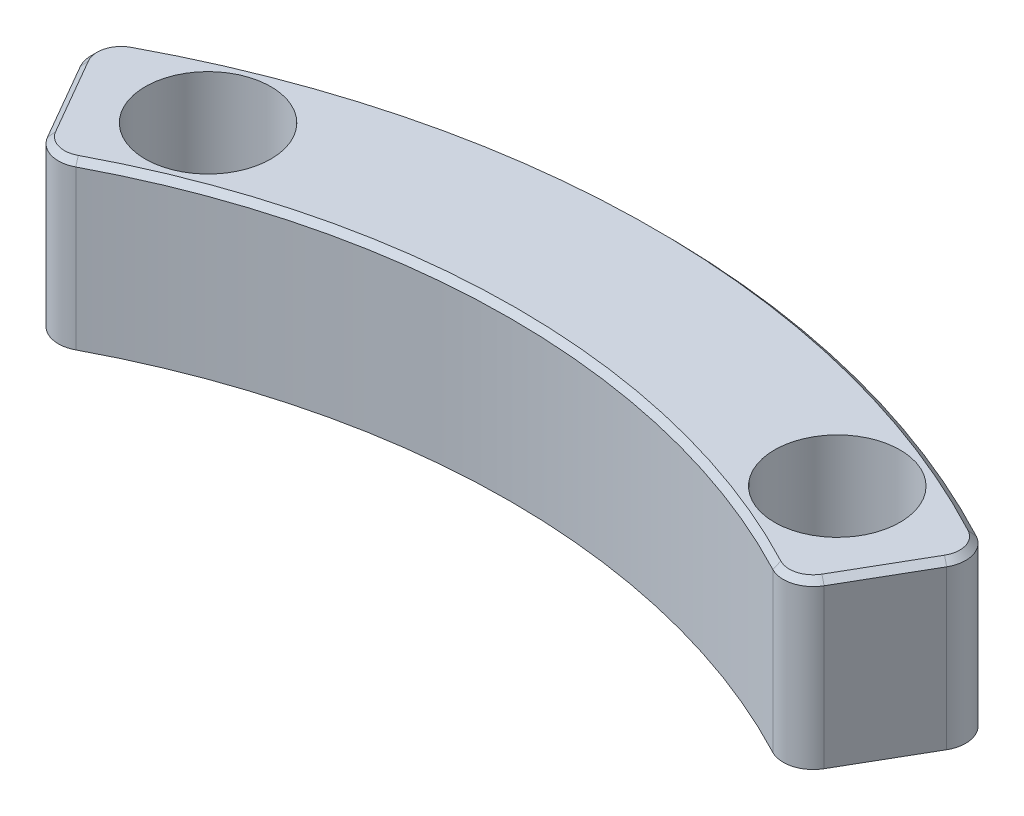
SolidWorks part; units mm, degrees
material "6061 合金"
ref_plane "前视基准面" through (0, 0, 0) normal (0, 0, 1) x (1, 0, 0)
ref_plane "上视基准面" through (0, 0, 0) normal (0, 1, 0) x (1, 0, 0)
ref_plane "右视基准面" through (0, 0, 0) normal (1, 0, 0) x (0, 0, -1)
other "Configuration Table"
sketch "草图1" plane through (0, 0, 0) normal (0, 1, 0) x (1, 0, 0)
  line L0 (0, 30) -> (0, 0) construction
  line L1 (0, 0) -> (-15, 25.9808) construction
  line L2 (0, 0) -> (15, 25.9808) construction
  line L3 (-15, 25.9808) -> (-12.5, 21.6506)
  line L4 (15, 25.9808) -> (12.5, 21.6506)
  arc A0 (15, 25.9808) -> (-15, 25.9808) centre (0, 0) ccw
  arc A1 (12.5, 21.6506) -> (-12.5, 21.6506) centre (0, 0) ccw
  dimension "D1" = 60
  dimension "D2" = 50
  dimension "D3" = 60
extrude "凸台-拉伸1" add sketch "草图1" along normal blind 5.5
sketch "草图2" plane through (0, 5.5, 0) normal (0, 1, 0) x (1, 0, 0)
  line L0 (0, 0) -> (-10.5238, 25.4067) construction
  line L1 (0, 27.5) -> (0, 0) construction
  line L2 (0, 0) -> (10.5238, 25.4067) construction
  circle A0 centre (0, 0) radius 27.5 construction
  circle A1 centre (-10.5238, 25.4067) radius 2.1
  circle A2 centre (10.5238, 25.4067) radius 2.1
  dimension "D1" = 55
  dimension "D3" = 4.2
  dimension "D4" = 4.2
  dimension "D2" = 45
extrude "切除-拉伸2" cut sketch "草图2" against normal blind 3
sketch "草图4" plane through (0, 5.5, 0) normal (0, 1, 0) x (1, 0, 0)
  circle A0 centre (-10.5238, 25.4067) radius 1.35
  circle A1 centre (10.5238, 25.4067) radius 1.35
  dimension "D1" = 2.7
  dimension "D2" = 2.7
extrude "切除-拉伸3" cut sketch "草图4" against normal blind 7
fillet "圆角2" radius 1 4 edges at (15, 2.75, -25.9808) (12.5, 2.75, -21.6506) (-15, 2.75, -25.9808) (-12.5, 2.75, -21.6506)
chamfer "倒角1" distance 0.2 angle 45 8 edges at (13.7409, 5.5, -23.7999) (14.5867, 5.5, -25.8752) (12.4017, 5.5, -22.0392) (0, 5.5, -30) (0, 5.5, -25) (-14.5867, 5.5, -25.8752) (-12.4017, 5.5, -22.0392) (-13.7409, 5.5, -23.7999)
